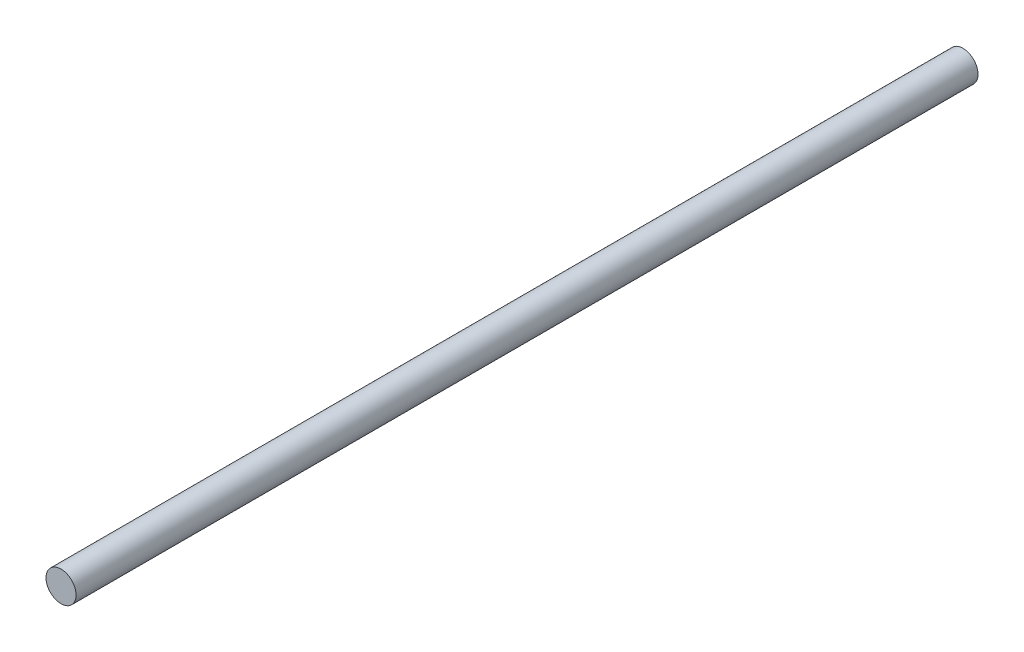
SolidWorks part; units mm, degrees
ref_plane "Plan de face" through (0, 0, 0) normal (0, 0, 1) x (1, 0, 0)
ref_plane "Plan de dessus" through (0, 0, 0) normal (0, 1, 0) x (1, 0, 0)
ref_plane "Plan de droite" through (0, 0, 0) normal (1, 0, 0) x (0, 0, -1)
sketch "Esquisse1" plane through (0, 0, 0) normal (0, 0, 1) x (1, 0, 0)
  circle A0 centre (0, 0) radius 1.5
  dimension "D1" = 3
extrude "Boss.-Extru.1" add sketch "Esquisse1" along normal blind 90
